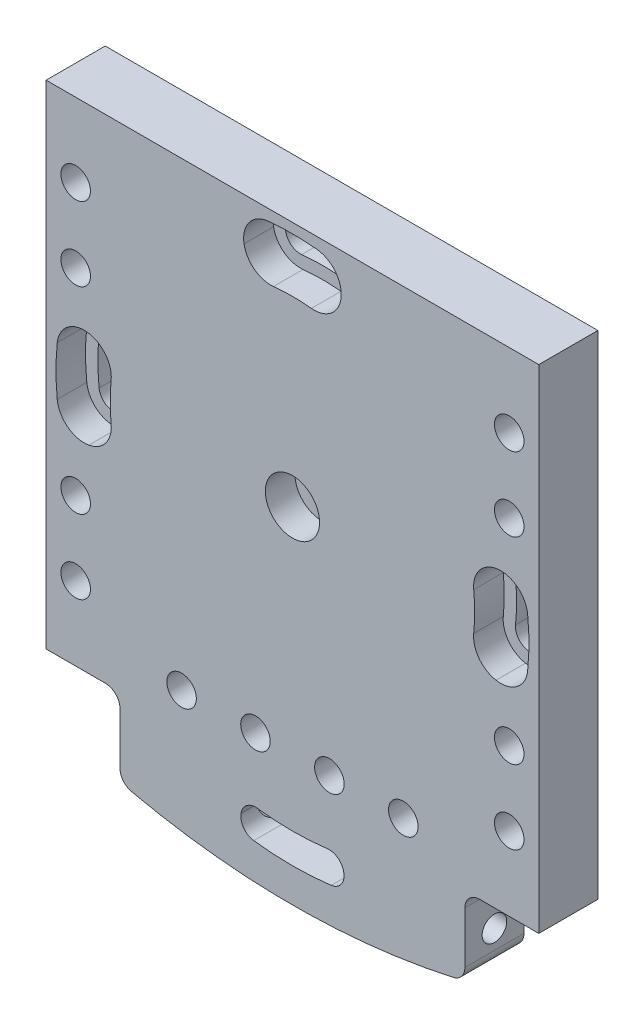
SolidWorks part; units mm, degrees
ref_plane "前视基准面" through (0, 0, 0) normal (0, 0, 1) x (1, 0, 0)
ref_plane "上视基准面" through (0, 0, 0) normal (0, 1, 0) x (1, 0, 0)
ref_plane "右视基准面" through (0, 0, 0) normal (1, 0, 0) x (0, 0, -1)
sketch "草图1" plane through (0, 0, 0) normal (0, 0, 1) x (1, 0, 0)
  line L0 (0, 0) -> (0, 80) construction
  line L1 (-50, 50) -> (50, 50)
  line L2 (-50, 48.957) -> (-50, -48.957)
  line L3 (-50, -50) -> (-37.992, -50)
  line L4 (50, 50) -> (50, -50)
  line L5 (-50, 50) -> (50, -50) construction
  line L6 (-50, -50) -> (50, 50) construction
  line L7 (-35, -52.992) -> (-35, -63.4811)
  line L8 (35, -52.992) -> (35, -63.4811)
  line L9 (37.992, -50) -> (50, -50)
  line L10 (-35, -50) -> (35, -50) construction
  line L11 (0, 0) -> (0.0006, -70) construction
  line L12 (0, 0) -> (-0.5209, -2.9544)
  line L13 (0, 0) -> (0.521, -2.9544)
  line L14 (-10.4037, -59.0053) -> (-10.4246, -59.1236)
  line L15 (-8.8159, -50) -> (-9.8975, -56.1341) construction
  line L16 (-0.5209, -2.9544) -> (-8.8159, -50) construction
  line L17 (10.4047, -59.0051) -> (10.4256, -59.1234)
  line L18 (8.8168, -50) -> (9.8984, -56.134) construction
  line L19 (0.521, -2.9544) -> (8.8168, -50) construction
  line L20 (0, 0) -> (-2.9544, -0.5209)
  line L21 (0, 0) -> (-2.9544, 0.5209)
  line L22 (-50, 0) -> (0, 0) construction
  line L23 (-41.7407, 7.36) -> (-41.7605, 7.3635)
  line L24 (-2.9544, 0.5209) -> (-38.8999, 6.8591) construction
  line L25 (-41.7407, -7.36) -> (-41.7605, -7.3635)
  line L26 (-2.9544, -0.5209) -> (-38.8999, -6.8591) construction
  line L27 (-7.36, 41.7407) -> (-7.3635, 41.7605)
  line L28 (7.36, 41.7407) -> (7.3635, 41.7605)
  line L29 (41.7407, 7.36) -> (41.7605, 7.3635)
  line L30 (41.7407, -7.36) -> (41.7605, -7.3635)
  line L31 (-50, -48.957) -> (-50, -50)
  line L32 (-50, 48.957) -> (-50, 50)
  arc A0 (-32.6594, -66.4014) -> (32.6594, -66.4014) centre (0, 80) ccw
  arc A1 (35, -65.8595) -> (-35, -65.8595) centre (0, 80) ccw construction
  arc A5 (37.992, -50) -> (35, -52.992) centre (37.992, -52.992) ccw
  arc A6 (35, -63.4811) -> (32.6594, -66.4014) centre (32.008, -63.4811) cw
  arc A7 (-32.6594, -66.4014) -> (-35, -63.4811) centre (-32.008, -63.4811) cw
  arc A8 (-37.992, -50) -> (-35, -52.992) centre (-37.992, -52.992) cw
  circle A10 centre (0, 0) radius 3
  circle A11 centre (0, -60) radius 3 construction
  arc A12 (7.8531, -62.6094) -> (-7.8521, -62.6095) centre (0, 0) cw
  arc A13 (7.0883, -56.5575) -> (-7.0874, -56.5577) centre (0, 0) cw
  arc A14 (10.4256, -59.1234) -> (7.8531, -62.6094) centre (7.481, -59.6427) cw
  arc A15 (10.4047, -59.0051) -> (7.0883, -56.5575) centre (7.4601, -59.5243) ccw
  arc A16 (-7.8521, -62.6095) -> (-10.4246, -59.1236) centre (-7.48, -59.6428) cw
  arc A17 (-7.0874, -56.5577) -> (-10.4037, -59.0053) centre (-7.4591, -59.5245) ccw
  circle A18 centre (-42.5, 0) radius 3 construction
  arc A21 (-45.2535, 4.7297) -> (-45.2535, -4.7297) centre (0, 0) ccw
  arc A22 (-39.2861, 4.1047) -> (-39.2861, -4.1047) centre (0, 0) ccw
  arc A23 (-45.2535, -4.7297) -> (-41.7605, -7.3635) centre (-42.2797, -4.4189) ccw
  arc A24 (-41.7407, -7.36) -> (-39.2861, -4.1047) centre (-42.26, -4.4154) ccw
  arc A25 (-41.7407, 7.36) -> (-39.2861, 4.1047) centre (-42.26, 4.4154) cw
  arc A26 (-41.7605, 7.3635) -> (-45.2535, 4.7297) centre (-42.2797, 4.4189) ccw
  arc A27 (-4.7297, 45.2535) -> (-7.3635, 41.7605) centre (-4.4189, 42.2797) ccw
  arc A28 (-7.36, 41.7407) -> (-4.1047, 39.2861) centre (-4.4154, 42.26) ccw
  arc A29 (4.1047, 39.2861) -> (-4.1047, 39.2861) centre (0, 0) ccw
  arc A30 (7.36, 41.7407) -> (4.1047, 39.2861) centre (4.4154, 42.26) cw
  arc A31 (7.3635, 41.7605) -> (4.7297, 45.2535) centre (4.4189, 42.2797) ccw
  arc A32 (4.7297, 45.2535) -> (-4.7297, 45.2535) centre (0, 0) ccw
  arc A33 (45.2535, 4.7297) -> (41.7605, 7.3635) centre (42.2797, 4.4189) ccw
  arc A34 (41.7407, 7.36) -> (39.2861, 4.1047) centre (42.26, 4.4154) ccw
  arc A35 (39.2861, -4.1047) -> (39.2861, 4.1047) centre (0, 0) ccw
  arc A36 (41.7407, -7.36) -> (39.2861, -4.1047) centre (42.26, -4.4154) cw
  arc A37 (41.7605, -7.3635) -> (45.2535, -4.7297) centre (42.2797, -4.4189) ccw
  arc A38 (45.2535, -4.7297) -> (45.2535, 4.7297) centre (0, 0) ccw
  point P0 (0, 0)
  point P4 (0, -70)
  point P52 (10.9577, -62.1413)
  point P79 (-44.8088, 7.901)
  dimension "D3" = 300
  dimension "D7" = 80
  dimension "D8" = 6
  dimension "D9" = 6
  dimension "D15" = 45.5
  dimension "D16" = 63.1
  dimension "D17" = 20
  dimension "D18" = 57
  dimension "D19" = 2.99
  dimension "D11" = 6
  dimension "D20" = 2.99
  dimension "D24" = 3
  dimension "D25" = 45.5
  dimension "D26" = 20
  dimension "D27" = 39.5
  dimension "D1" = 100
  dimension "D2" = 100
  dimension "D4" = 20
  dimension "D5" = 15
  dimension "D6" = 15
  dimension "D10" = 60
  dimension "D12" = 63.1
  dimension "D13" = 10
  dimension "D14" = 10
  dimension "D21" = 10
  dimension "D22" = 10
  dimension "D23" = 42.5
extrude "凸台-拉伸1" add sketch "草图1" along normal blind 12
sketch "草图2" plane through (-35, 0, 0) normal (-1, 0, 0) x (0, 0, 1)
  line L0 (12, -52.992) -> (0, -52.992) construction
  circle A0 centre (6, -59.592) radius 2.5
  dimension "D1" = 5
  dimension "D2" = 6.6
extrude "切除-拉伸1" cut sketch "草图2" against normal blind 100
sketch "草图4" plane through (0, 0, 12) normal (0, 0, 1) x (1, 0, 0)
  line L14 (-9.8255, 41.3264) -> (-9.822, 41.3066)
  line L15 (9.822, 41.3066) -> (9.8255, 41.3264)
  line L16 (-41.3264, -9.8255) -> (-41.3066, -9.822)
  line L17 (-41.3066, 9.822) -> (-41.3264, 9.8255)
  line L18 (-41.3264, -9.8255) -> (-41.3066, -9.822)
  line L19 (-41.3066, 9.822) -> (-41.3264, 9.8255)
  line L20 (41.3264, 9.8255) -> (41.3066, 9.822)
  line L21 (41.3066, -9.822) -> (41.3264, -9.8255)
  circle A2 centre (0, 0) radius 5.5
  circle A3 centre (0, 0) radius 5.5
  arc A71 (-9.822, 41.3066) -> (-3.8449, 36.7997) centre (-4.4154, 42.26) ccw
  arc A72 (-4.9896, 47.74) -> (-9.8255, 41.3264) centre (-4.4189, 42.2797) ccw
  arc A73 (4.9896, 47.74) -> (-4.9896, 47.74) centre (0, 0) ccw
  arc A74 (9.8255, 41.3264) -> (4.9896, 47.74) centre (4.4189, 42.2797) ccw
  arc A75 (3.8449, 36.7997) -> (9.822, 41.3066) centre (4.4154, 42.26) ccw
  arc A76 (3.8449, 36.7997) -> (-3.8449, 36.7997) centre (0, 0) ccw
  arc A77 (-41.3066, -9.822) -> (-36.7997, -3.8449) centre (-42.26, -4.4154) ccw
  arc A78 (-47.74, -4.9896) -> (-41.3264, -9.8255) centre (-42.2797, -4.4189) ccw
  arc A79 (-47.74, 4.9896) -> (-47.74, -4.9896) centre (0, 0) ccw
  arc A80 (-41.3264, 9.8255) -> (-47.74, 4.9896) centre (-42.2797, 4.4189) ccw
  arc A81 (-36.7997, 3.8449) -> (-41.3066, 9.822) centre (-42.26, 4.4154) ccw
  arc A82 (-36.7997, 3.8449) -> (-36.7997, -3.8449) centre (0, 0) ccw
  arc A83 (-41.3066, -9.822) -> (-36.7997, -3.8449) centre (-42.26, -4.4154) ccw
  arc A84 (-47.74, -4.9896) -> (-41.3264, -9.8255) centre (-42.2797, -4.4189) ccw
  arc A85 (-47.74, 4.9896) -> (-47.74, -4.9896) centre (0, 0) ccw
  arc A86 (-41.3264, 9.8255) -> (-47.74, 4.9896) centre (-42.2797, 4.4189) ccw
  arc A87 (-36.7997, 3.8449) -> (-41.3066, 9.822) centre (-42.26, 4.4154) ccw
  arc A88 (-36.7997, 3.8449) -> (-36.7997, -3.8449) centre (0, 0) ccw
  arc A89 (41.3066, 9.822) -> (36.7997, 3.8449) centre (42.26, 4.4154) ccw
  arc A90 (47.74, 4.9896) -> (41.3264, 9.8255) centre (42.2797, 4.4189) ccw
  arc A91 (47.74, -4.9896) -> (47.74, 4.9896) centre (0, 0) ccw
  arc A92 (41.3264, -9.8255) -> (47.74, -4.9896) centre (42.2797, -4.4189) ccw
  arc A93 (36.7997, -3.8449) -> (41.3066, -9.822) centre (42.26, -4.4154) ccw
  arc A94 (36.7997, -3.8449) -> (36.7997, 3.8449) centre (0, 0) ccw
  dimension "D1" = 2.5
  dimension "D3" = 2.5
  dimension "D2" = 3
extrude "切除-拉伸2" cut sketch "草图4" against normal blind 6
sketch "草图5" plane through (0, 0, 0) normal (0, 0, -1) x (-1, 0, 0)
  line L0 (0, 0) -> (0, 32.3811) construction
  line L1 (44, -41.5307) -> (44, -8.8104) construction
  line L2 (50, -50) -> (37.992, -50) construction
  line L3 (0, 0) -> (26.9118, 0) construction
  line L4 (50, 50) -> (50, -50) construction
  circle A0 centre (44, -35) radius 3
  circle A4 centre (44, -20) radius 3
  circle A7 centre (44, 35) radius 3
  circle A8 centre (44, 20) radius 3
  circle A9 centre (-44, 20) radius 3
  circle A10 centre (-44, 35) radius 3
  circle A11 centre (-44, -20) radius 3
  circle A12 centre (-44, -35) radius 3
  dimension "D1" = 6
  dimension "D2" = 6
  dimension "D3" = 15
  dimension "D4" = 15
  dimension "D5" = 6
extrude "切除-拉伸3" cut sketch "草图5" against normal blind 12
sketch "草图6" plane through (0, 0, 0) normal (0, 0, -1) x (-1, 0, 0)
  line L0 (16.5834, 0) -> (0, 0) construction
  line L1 (0, 0) -> (0, 24.481) construction
  circle A2 centre (44, -35) radius 5.5
  circle A3 centre (44, -35) radius 5.5
  circle A4 centre (44, 20) radius 5.5
  circle A5 centre (44, -20) radius 5.5
  circle A6 centre (44, -20) radius 5.5
  circle A7 centre (44, 35) radius 5.5
  circle A8 centre (-44, 35) radius 5.5
  circle A9 centre (-44, -20) radius 5.5
  circle A10 centre (-44, 20) radius 5.5
  circle A11 centre (-44, -35) radius 5.5
  dimension "D1" = 2.5
  dimension "D2" = 2.5
extrude "切除-拉伸4" cut sketch "草图6" against normal blind 6
sketch "草图7" plane through (0, 0, 0) normal (0, 0, -1) x (-1, 0, 0)
  line L0 (50, -50) -> (50, 50) construction
  circle A0 centre (22.5, -43.4934) radius 3
  circle A1 centre (7.5, -43.4934) radius 3
  circle A2 centre (-7.5, -43.4934) radius 3
  circle A3 centre (-22.5, -43.4934) radius 3
  dimension "D1" = 6
  dimension "D2" = 27.5
  dimension "D3" = 4
extrude "切除-拉伸5" cut sketch "草图7" against normal blind 12
sketch "草图8" plane through (0, 0, 0) normal (0, 0, -1) x (-1, 0, 0)
  circle A1 centre (7.5, -43.4934) radius 5.5
  circle A2 centre (22.5, -43.4934) radius 5.5
  circle A3 centre (22.5, -43.4934) radius 5.5
  circle A4 centre (-7.5, -43.4934) radius 5.5
  circle A5 centre (-22.5, -43.4934) radius 5.5
  dimension "D1" = 2.5
  dimension "D2" = 4
extrude "切除-拉伸6" cut sketch "草图8" against normal blind 6
equation "\"100、\"=94.4378"
equation "\"20、\"=25.4335"
